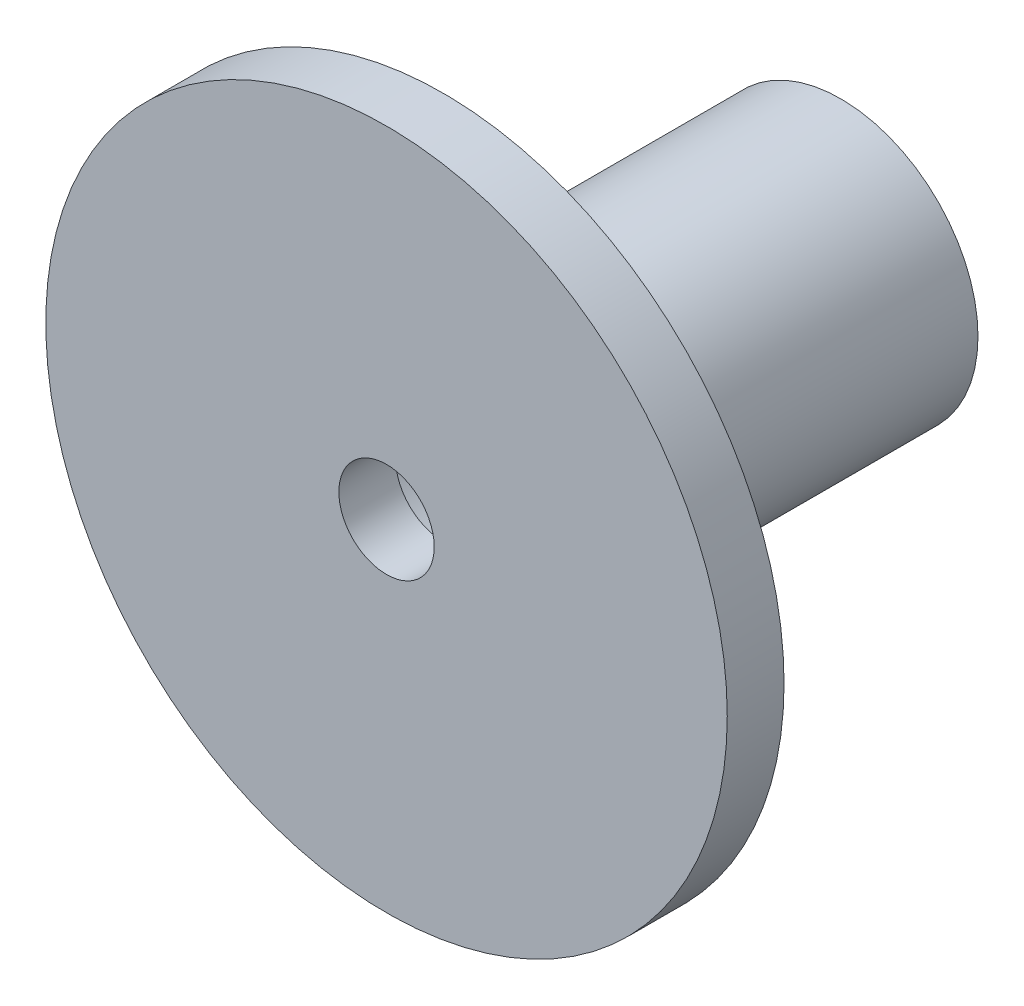
SolidWorks part; units mm, degrees
ref_plane "Front Plane" through (0, 0, 0) normal (0, 0, 1) x (1, 0, 0)
ref_plane "Top Plane" through (0, 0, 0) normal (0, 1, 0) x (1, 0, 0)
ref_plane "Right Plane" through (0, 0, 0) normal (1, 0, 0) x (0, 0, -1)
sketch "Sketch1" plane through (0, 0, 0) normal (0, 0, 1) x (1, 0, 0)
  circle A0 centre (0, 0) radius 40
  circle A1 centre (0, 0) radius 24.15
  circle A2 centre (0, 0) radius 20.3
  dimension "D1" = 80
  dimension "D2" = 48.3
  dimension "D3" = 40.6
extrude "Boss-Extrude1" add sketch "Sketch1" along normal blind 70 contours A1 A2
sketch "Sketch2" plane through (0, 0, 70) normal (0, 0, 1) x (1, 0, 0)
  circle A0 centre (0, 0) radius 40
  circle A1 centre (0, 0) radius 8.4
  circle A2 centre (0, 0) radius 21.65
  circle M1 centre (0, 0) radius 20.3
  dimension "D1" = 80
  dimension "D2" = 16.8
  dimension "D3" = 43.3
extrude "Cut-Extrude1" cut sketch "Sketch2" against normal blind 3.2 contours A2 M1
sketch "Sketch3" plane through (0, 0, 70) normal (0, 0, 1) x (1, 0, 0)
  circle A0 centre (0, 0) radius 60
  circle A1 centre (0, 0) radius 8.4
  dimension "D1" = 120
  dimension "D2" = 16.8
extrude "Boss-Extrude2" add sketch "Sketch3" along normal blind 10
